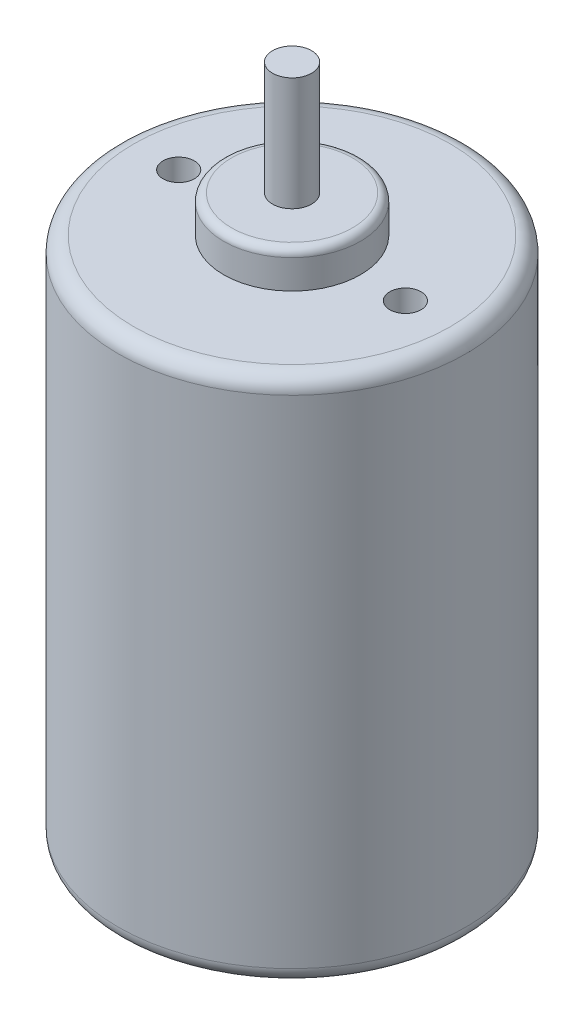
SolidWorks part; units mm, degrees
ref_plane "Front Plane" through (0, 0, 0) normal (0, 0, 1) x (1, 0, 0)
ref_plane "Top Plane" through (0, 0, 0) normal (0, 1, 0) x (1, 0, 0)
ref_plane "Right Plane" through (0, 0, 0) normal (1, 0, 0) x (0, 0, -1)
sketch "Sketch1" plane through (0, 0, 0) normal (0, 1, 0) x (1, 0, 0)
  circle A0 centre (0, 0) radius 22.25
extrude "Boss-Extrude1" add sketch "Sketch1" along normal blind 67.5
sketch "Sketch2" plane through (0, 67.5, 0) normal (0, 1, 0) x (1, 0, 0)
  circle A0 centre (0, 0) radius 8.75
extrude "Boss-Extrude2" add sketch "Sketch2" along normal blind 4.7
sketch "Sketch3" plane through (0, 72.2, 0) normal (0, 1, 0) x (1, 0, 0)
  circle A0 centre (0, 0) radius 2.5
extrude "Boss-Extrude3" add sketch "Sketch3" along normal blind 14.5
sketch "Sketch4" plane through (0, 67.5, 0) normal (0, 1, 0) x (1, 0, 0)
  circle A0 centre (0, 0) radius 14.5 construction
  circle A1 centre (14.5, 0) radius 2
  circle A2 centre (-14.5, 0) radius 2
extrude "Cut-Extrude1" cut sketch "Sketch4" against normal blind 14.5
fillet "Fillet1" radius 2 2 edges at (0, 0, 22.25) (0, 67.5, 22.25)
fillet "Fillet2" radius 1 1 edges at (0, 72.2, 8.75)
